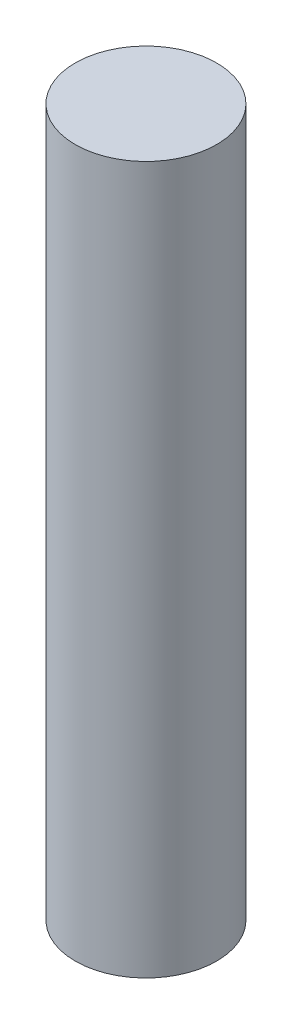
SolidWorks part; units mm, degrees
material "Plain Carbon Steel"
ref_plane "Front Plane" through (0, 0, 0) normal (0, 0, 1) x (1, 0, 0)
ref_plane "Top Plane" through (0, 0, 0) normal (0, 1, 0) x (1, 0, 0)
ref_plane "Right Plane" through (0, 0, 0) normal (1, 0, 0) x (0, 0, -1)
sketch "Sketch1" plane through (0, 0, 0) normal (0, 1, 0) x (1, 0, 0)
  circle A0 centre (0, 0) radius 6
  dimension "D1" = 12
extrude "Boss-Extrude1" add sketch "Sketch1" along normal blind 60
